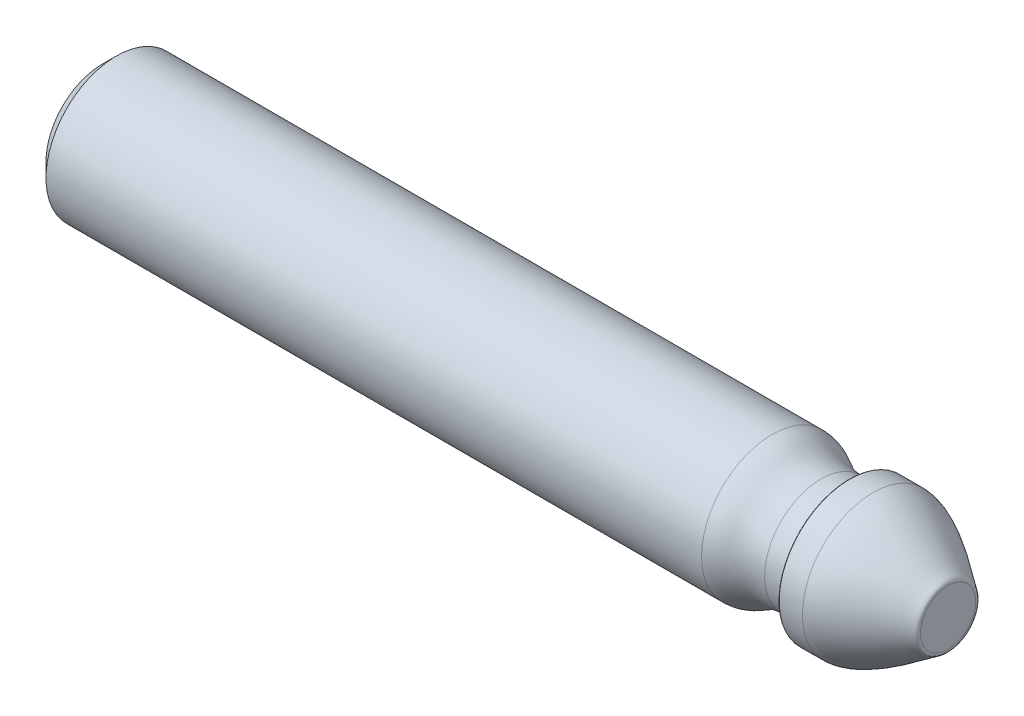
SolidWorks part; units mm, degrees
material "Alloy Steel"
ref_plane "Front" through (0, 0, 0) normal (0, 0, 1) x (1, 0, 0)
ref_plane "Top" through (0, 0, 0) normal (0, 1, 0) x (1, 0, 0)
ref_plane "Right" through (0, 0, 0) normal (1, 0, 0) x (0, 0, -1)
sketch "Sketch1" plane through (0, 0, 0) normal (0, 0, 1) x (1, 0, 0)
  line L0 (-19.05, 0) -> (19.05, 0) construction
  line L1 (19.05, 3.175) -> (19.05, -3.175) construction
  line L2 (-19.05, 3.175) -> (-19.05, -3.175) construction
  dimension "Length" = 38.1
  dimension "Diameter" = 6.35
sketch "Sketch2" plane through (0, 0, 0) normal (1, 0, 0) x (0, 0, -1)
  circle A0 centre (0, 0) radius 3.175
extrude "Extrude1" add sketch "Sketch2" against normal up to vertex (19.05 mm away) and the other way up to vertex (19.05 mm away) up to point (-19.05, 3.175, 0) other way up to point (19.05, 3.175, 0)
chamfer "Chamfer1" distance 0.635 angle 45 2 edges at (19.05, 0, -3.175) (-19.05, 0, -3.175)
sketch "Sketch3" plane through (0, 0, 0) normal (0, 0, 1) x (1, 0, 0)
  line L0 (-19.05, 0) -> (19.05, 0) construction
  line L1 (-19.05, 2.54) -> (-19.05, -2.54) construction
  line L2 (19.05, -2.54) -> (19.05, 2.54) construction
  line L3 (18.415, 3.175) -> (-18.415, 3.175) construction
  line L4 (15.6622, 3.175) -> (14.5934, 3.175)
  line L5 (16.629, 3.175) -> (14.655, 3.175) construction
  line L6 (19.05, 0.802) -> (19.05, 1.6965) construction
  line L7 (19.05, 1.2434) -> (19.05, 3.175)
  line L8 (19.05, 3.175) -> (15.6622, 3.175)
  line L9 (14.5934, 3.175) -> (14.5934, 2.54)
  line L10 (14.5934, 2.54) -> (13.3234, 2.54)
  line L11 (11.1187, 3.175) -> (14.5934, 3.175)
  line L12 (11.6265, 3.175) -> (9.464, 3.175) construction
  line L13 (14.3233, 2.54) -> (12.3233, 2.54) construction
  line L14 (11.1187, 3.175) -> (14.5934, 3.175)
  spline S0 degree 3 poles (15.6622, 3.175) (16.6428, 3.175) (18.614, 1.6311) (19.0441, 1.3825) (19.05, 1.3487) (19.05, 1.2434) knots 0 0 0 0 0.565725 0.665725 1 1 1 1
  spline S1 degree 3 poles (11.1187, 3.175) (11.9879, 3.175) (12.0734, 2.54) (13.3234, 2.54) knots 0 0 0 0 1 1 1 1
revolve "Cut-Revolve1" cut sketch "Sketch3" angle 360 about L0
fillet "Fillet1" radius 0.0254 1 edges at (14.5934, 0, 3.175)
equation "\"D1@Chamfer1\" = \"Diameter@Sketch1\"*.1"
